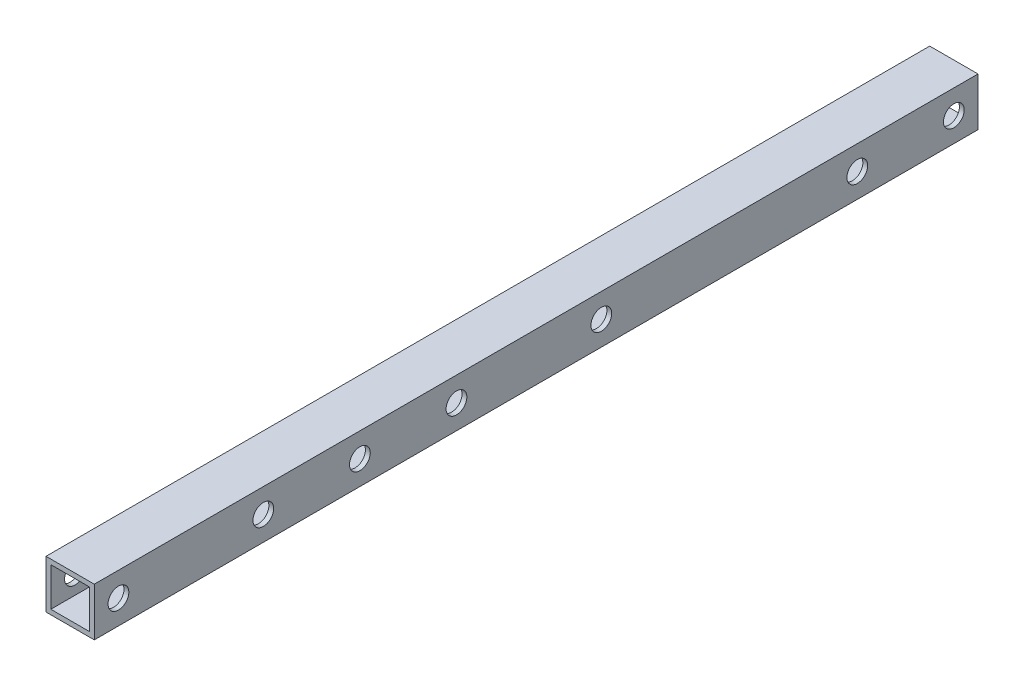
SolidWorks part; units mm, degrees
material "5052-H34"
ref_plane "正面" through (0, 0, 0) normal (0, 0, 1) x (1, 0, 0)
ref_plane "平面" through (0, 0, 0) normal (0, 1, 0) x (1, 0, 0)
ref_plane "右側面" through (0, 0, 0) normal (1, 0, 0) x (0, 0, -1)
sketch "ｽｹｯﾁ1" plane through (0, 0, 0) normal (0, 0, 1) x (1, 0, 0)
  line L1 (-5, 5) -> (5, 5)
  line L2 (-5, 5) -> (-5, -5)
  line L3 (-5, -5) -> (5, -5)
  line L4 (5, 5) -> (5, -5)
  line L5 (-5, 5) -> (5, -5) construction
  line L6 (-5, -5) -> (5, 5) construction
  point P0 (0, 0)
  dimension "D1" = 10
  dimension "D2" = 10
extrude "押し出し-薄板1" add sketch "ｽｹｯﾁ1" along normal blind 183 thin
sketch "ｽｹｯﾁ2" plane through (5, 0, 0) normal (1, 0, 0) x (0, 0, -1)
  line L0 (-128, 5) -> (-128, -5) construction
  line L1 (-183, 5) -> (0, 5) construction
  line L2 (-183, -5) -> (0, -5) construction
  line L3 (-128, 0) -> (-108, 0) construction
  line L5 (-128, 0) -> (-178, 0) construction
  line L8 (-128, 5) -> (-128, -5) construction
  line L9 (0, -5) -> (0, 5) construction
  circle A0 centre (-128, 0) radius 2.15
  circle A1 centre (-108, 0) radius 2.15
  circle A2 centre (-148, 0) radius 2.15
  circle A3 centre (-178, 0) radius 2.15
  circle A4 centre (-78, 0) radius 2.15
  circle A12 centre (-5, 0) radius 2.15
  circle A13 centre (-25, 0) radius 2.15
  dimension "D1" = 4.3
  dimension "D4" = 4.3
  dimension "D9" = 20
  dimension "D3" = 5
  dimension "D2" = 40
  dimension "D5" = 128
  dimension "D6" = 50
extrude "ｶｯﾄ - 押し出し1" cut sketch "ｽｹｯﾁ2" against normal through all
sketch "ｽｹｯﾁ3" plane through (0, 5, 0) normal (0, 1, 0) x (1, 0, 0)
  line L0 (0, 0) -> (0, -183) construction
  line L1 (5, -183) -> (-5, -183) construction
  line L2 (5, -91.5) -> (-5, -91.5) construction
  line L3 (5, -183) -> (5, 0) construction
  line L4 (-5, -183) -> (-5, 0) construction
  line L5 (5, 0) -> (-5, 0) construction
  circle A0 centre (0, -5) radius 2.15
  circle A1 centre (0, -25) radius 2.15
  dimension "D1" = 4.3
  dimension "D2" = 5
  dimension "D3" = 20
extrude "ｶｯﾄ - 押し出し2" [suppressed] cut sketch "ｽｹｯﾁ3" against normal up to surface (10 mm away)
